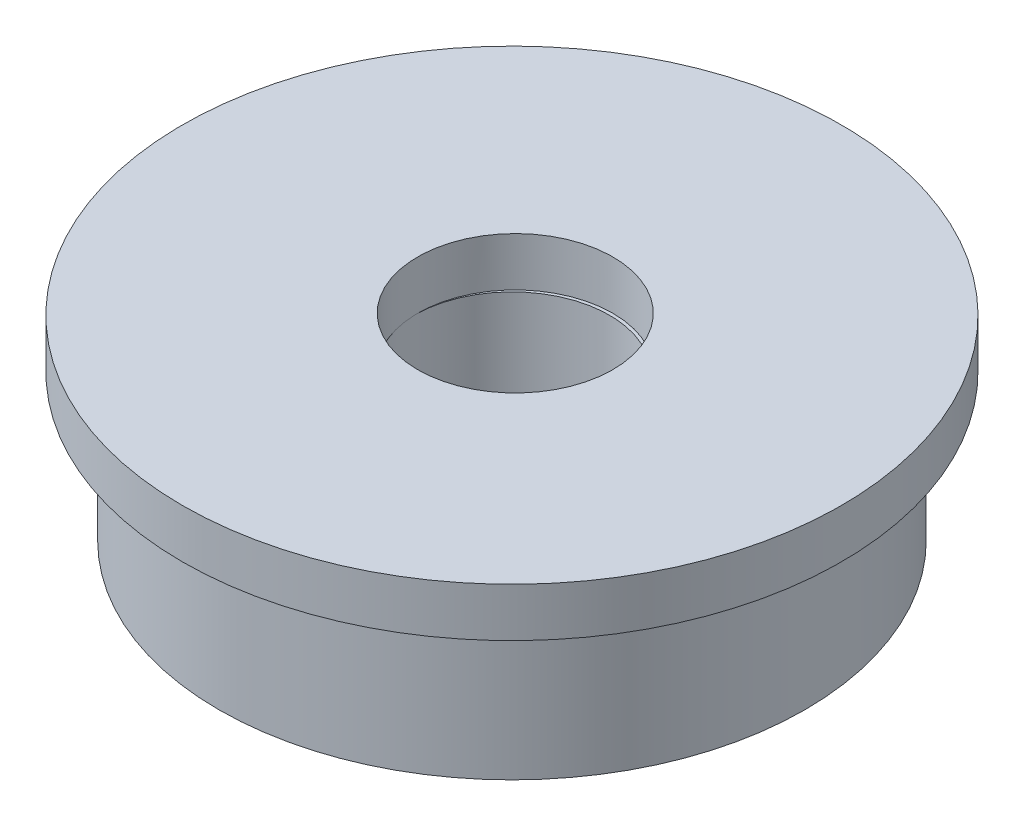
SolidWorks part; units mm, degrees
ref_plane "前视基准面" through (0, 0, 0) normal (0, 0, 1) x (1, 0, 0)
ref_plane "上视基准面" through (0, 0, 0) normal (0, 1, 0) x (1, 0, 0)
ref_plane "右视基准面" through (0, 0, 0) normal (1, 0, 0) x (0, 0, -1)
other "Configuration Table"
sketch "草图1" plane through (0, 0, 0) normal (0, 1, 0) x (1, 0, 0)
  circle A0 centre (0, 0) radius 2
  circle A1 centre (0, 0) radius 6
  dimension "D1" = 12
  dimension "D2" = 4
extrude "凸台-拉伸1" add sketch "草图1" along normal blind 3
sketch "草图2" plane through (0, 3, 0) normal (0, 1, 0) x (1, 0, 0)
  circle A0 centre (0, 0) radius 6.75
  circle A1 centre (0, 0.0678) radius 2
  dimension "D1" = 13.5
  dimension "D2" = 4
extrude "凸台-拉伸2" add sketch "草图2" along normal blind 1
